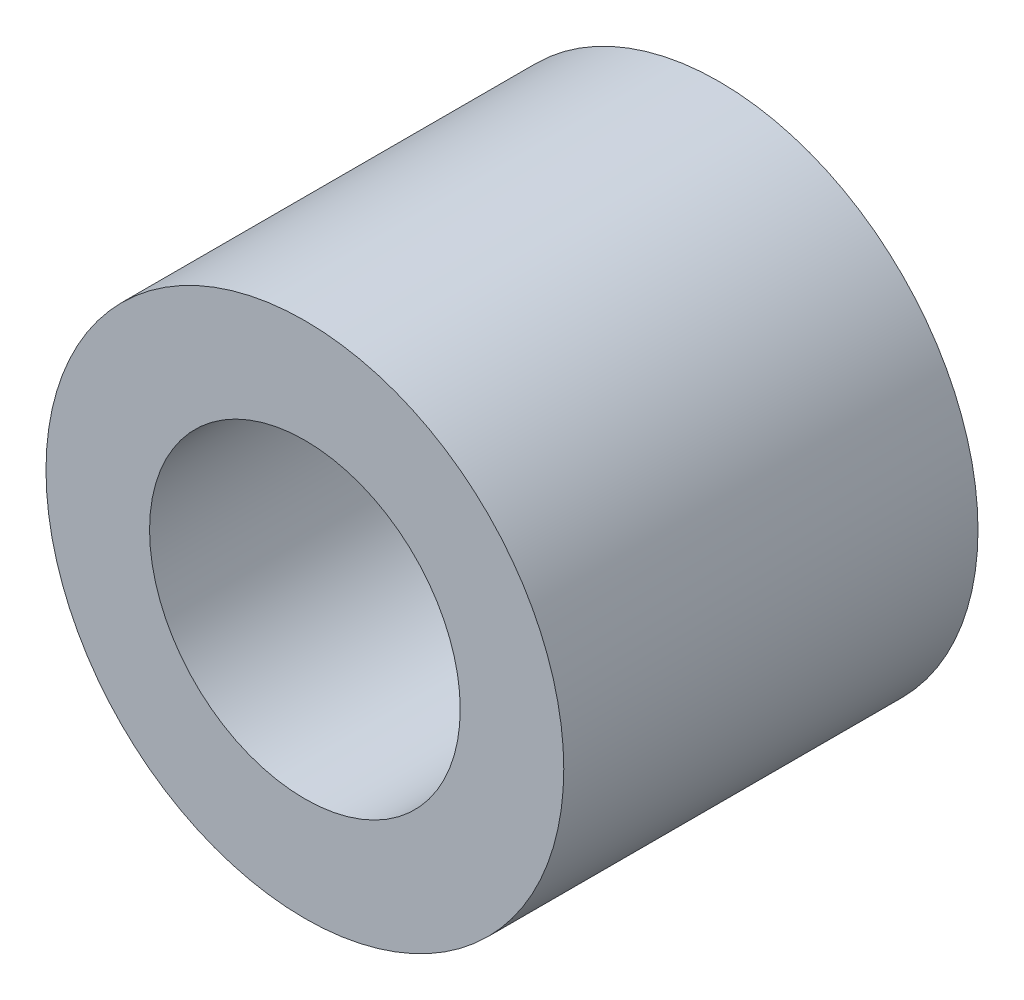
SolidWorks part; units mm, degrees
material "Vero PureWhite"
ref_plane "前视基准面" through (0, 0, 0) normal (0, 0, 1) x (1, 0, 0)
ref_plane "上视基准面" through (0, 0, 0) normal (0, 1, 0) x (1, 0, 0)
ref_plane "右视基准面" through (0, 0, 0) normal (1, 0, 0) x (0, 0, -1)
sketch "草图1" plane through (0, 0, 0) normal (0, 0, 1) x (1, 0, 0)
  circle A0 centre (0, 0) radius 1.5
  circle A1 centre (0, 0) radius 2.5
  dimension "D1" = 3
  dimension "D2" = 5
extrude "凸台-拉伸1" add sketch "草图1" along normal blind 4
scale "缩放比例1" scale about origin uniform scaling yes scale factor 0.6
